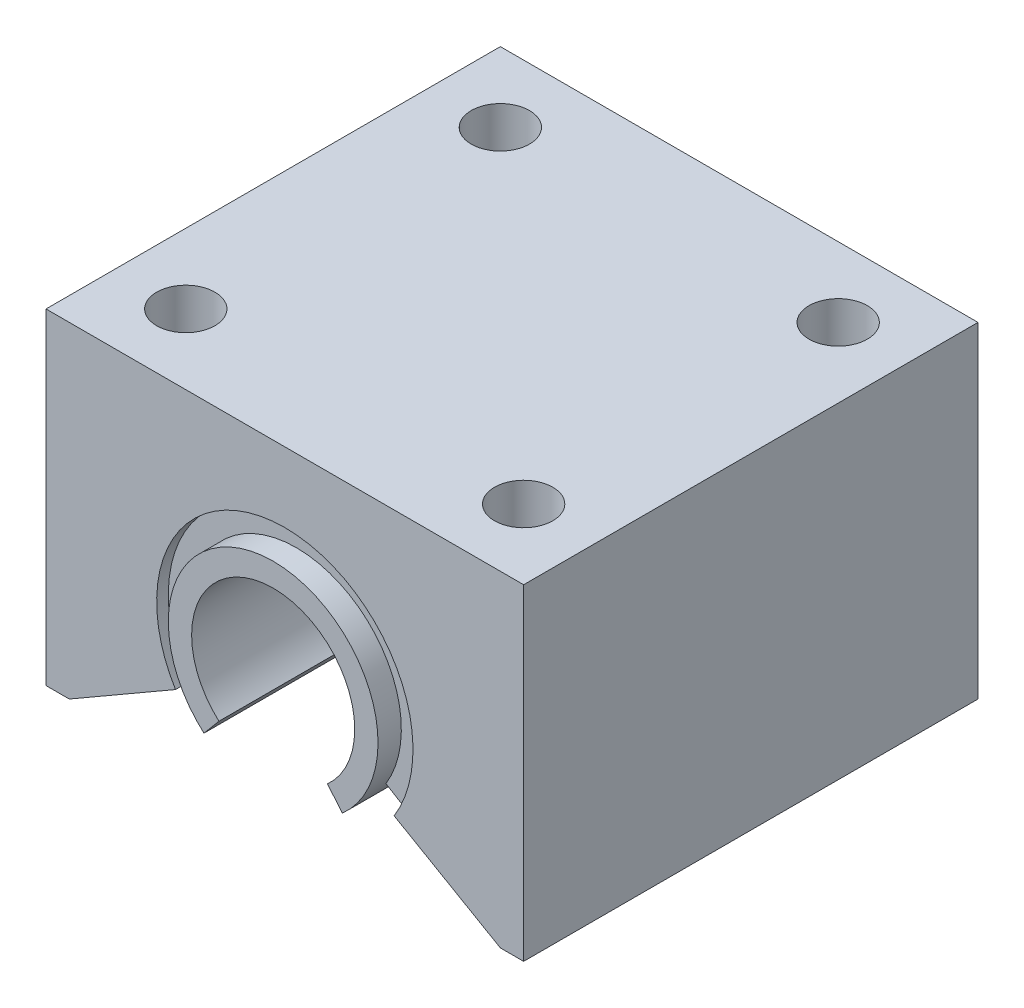
SolidWorks part; units mm, degrees
ref_plane "Front Plane" through (0, 0, 0) normal (0, 0, 1) x (1, 0, 0)
ref_plane "Top Plane" through (0, 0, 0) normal (0, 1, 0) x (1, 0, 0)
ref_plane "Right Plane" through (0, 0, 0) normal (1, 0, 0) x (0, 0, -1)
sketch "Sketch1" plane through (0, 0, 0) normal (0, 0, 1) x (1, 0, 0)
  line L1 (-20.5, 14) -> (20.5, 14)
  line L2 (-20.5, 14) -> (-20.5, -14)
  line L3 (-20.5, -14) -> (-18.5, -14)
  line L4 (20.5, 14) -> (20.5, -14)
  line L5 (-20.5, 14) -> (20.5, -14) construction
  line L6 (-20.5, -14) -> (20.5, 14) construction
  line L7 (0, 0) -> (0, -20.1822) construction
  line L9 (-18.5, -14) -> (-9.3851, -8.7375)
  line L10 (18.5, -14) -> (9.3851, -8.7375)
  line L11 (18.5, -14) -> (20.5, -14)
  arc A0 (9.3851, -8.7375) -> (-9.3851, -8.7375) centre (0, -3) ccw
  point P0 (0, 0)
  dimension "D3" = 11
  dimension "D1" = 41
  dimension "D2" = 28
  dimension "D4" = 2
extrude "Boss-Extrude1" add sketch "Sketch1" along normal blind 39
sketch "Sketch2" plane through (0, 0, 0) normal (0, 0, 1) x (1, 0, 0)
  line L0 (-9.3851, -8.7375) -> (-7.6787, -7.6943)
  line L2 (9.3851, -8.7375) -> (7.6787, -7.6943)
  arc A0 (9.3851, -8.7375) -> (-9.3851, -8.7375) centre (0, -3) ccw
  arc A1 (7.6787, -7.6943) -> (-7.6787, -7.6943) centre (0, -3) ccw
  circle A3 centre (0, -3) radius 9 construction
  circle A4 centre (0, -3) radius 11 construction
  point P4 (10.5194, 0.2161)
  point P11 (9, -3)
  dimension "D1" = 2
extrude "Boss-Extrude3" add sketch "Sketch2" along normal blind 37 from offset 1 separate body
sketch "Sketch3" plane through (0, 0, 0) normal (0, 0, 1) x (1, 0, 0)
  line L0 (0, -3) -> (0, -16.4583) construction
  line L1 (-5.9419, -9.7597) -> (-4.6559, -8.2271)
  line L2 (5.9419, -9.7597) -> (4.6559, -8.2271)
  arc A0 (5.9419, -9.7597) -> (-5.9419, -9.7597) centre (0, -3) ccw
  arc A1 (4.6559, -8.2271) -> (-4.6559, -8.2271) centre (0, -3) ccw
  circle A3 centre (0, -3) radius 7 construction
  circle A4 centre (0, -3) radius 9 construction
  point P5 (8.6067, -0.3687)
  point P6 (7, -3)
  dimension "D1" = 2
extrude "Boss-Extrude4" add sketch "Sketch3" along normal blind 41 from offset 1 offset against normal yes
sketch "Sketch4" plane through (0, 14, 0) normal (0, 1, 0) x (1, 0, 0)
  line L0 (20.5, -39) -> (-20.5, -39) construction
  line L5 (20.5, -39) -> (20.5, 0) construction
  circle A0 centre (-14.5, -6) radius 2.5
  circle A1 centre (14.5, -6) radius 2.5
  circle A2 centre (14.5, -33) radius 2.5
  circle A3 centre (-14.5, -33) radius 2.5
  point P13 (-20.5, -31.5558)
  point P14 (-20.5, -30.3839)
  dimension "D1" = 5
  dimension "D2" = 6
  dimension "D3" = 6
  dimension "D6" = 6
  dimension "D7" = 6
  dimension "D8" = 27
  dimension "D9" = 29
  dimension "D4" = 2
  dimension "D5" = 2
extrude "Cut-Extrude1" cut sketch "Sketch4" against normal blind 10
hole_wizard "Tap Drill for M5x0.8 Tap1" positions "Sketch7" profile "Sketch8" hole size "M5x0.8" standard "ANSI Metric"
sketch "Sketch7" plane through (0, 4, 0) normal (0, 1, 0) x (1, 0, 0)
  point P0 (-14.5, -33)
  point P3 (-14.5, -6)
  point P6 (14.5, -6)
  point P9 (14.5, -33)
sketch "Sketch8" plane through (-14.5, 4, 33) normal (1, 0, 0) x (0, 0, 1)
  line L0 (0, 0) -> (0, 1.3118)
  line L1 (0, 1.3118) -> (2.1, 0.05)
  line L2 (2.1, 0.05) -> (2.1, 0.025)
  line L3 (2.1, 0.025) -> (2.125, 0)
  line L5 (2.125, 0) -> (0, 0)
  line L6 (-2.1, 0.025) -> (-2.125, 0) construction
  line L10 (0, 1.3118) -> (-2.1, 0.05) construction
  line L11 (0, -6.35) -> (0, 107.95) construction
  dimension "Hole Dia." = 4.2
  dimension "Hole Depth" = 0.05
  dimension "Near C'Sink Dia." = 4.25
  dimension "Near C'Sink Angle" = 90
  dimension "Drill Angle" = 118
